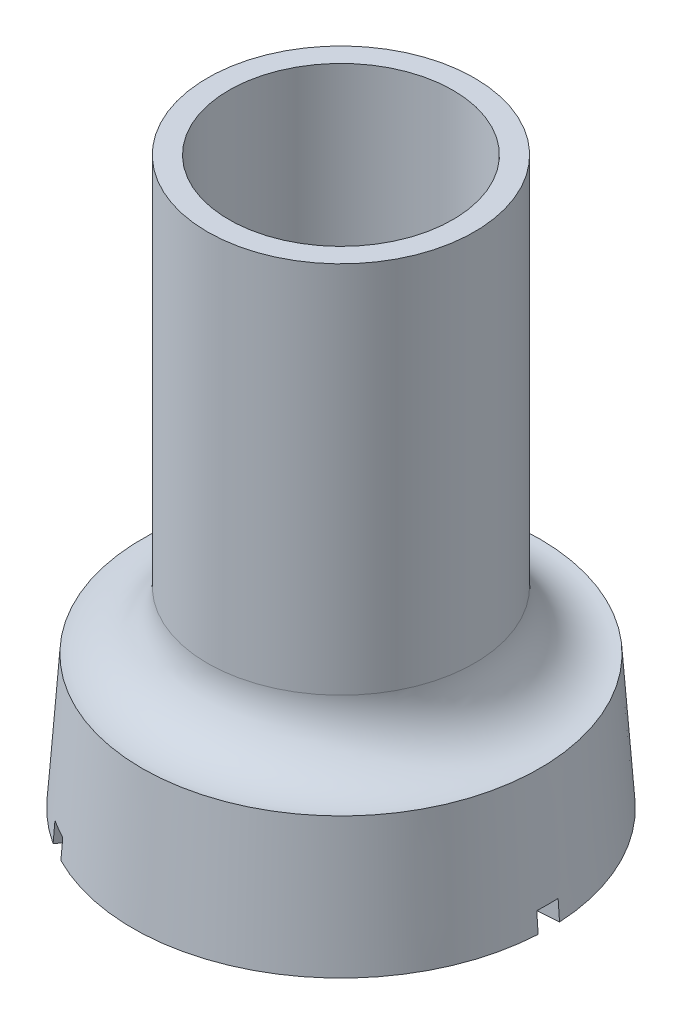
SolidWorks part; units mm, degrees
ref_plane "Płaszczyzna przednia" through (0, 0, 0) normal (0, 0, 1) x (1, 0, 0)
ref_plane "Płaszczyzna górna" through (0, 0, 0) normal (0, 1, 0) x (1, 0, 0)
ref_plane "Płaszczyzna prawa" through (0, 0, 0) normal (1, 0, 0) x (0, 0, -1)
sketch "Szkic2" plane through (0, 0, 0) normal (1, 0, 0) x (0, 0, -1)
  line L0 (0, 0) -> (0, 5.3) construction
  line L1 (0, 0) -> (1.95, 0) construction
  line L2 (1.95, 0) -> (1.7747, 2.5071) construction
  line L3 (0, 5.3) -> (1.25, 5.3) construction
  line L4 (1.25, 5.3) -> (1.25, 1.8)
  line L5 (1.8623, 1.2535) -> (1.95, 0)
  arc A0 (1.25, 1.8) -> (1.8623, 1.2535) centre (1.8, 1.8) ccw
  dimension "D6" = 0.55
  dimension "D1" = 5.3
  dimension "D2" = 1.95
  dimension "D3" = 4
  dimension "D4" = 1.25
  dimension "D5" = 3.5
revolve "Obrót-cienka ścianka3" add sketch "Szkic2" angle 360 about L0
sketch3d "Szkic 3D1"
  point P0 (1.687, 0.2884, -0.9372)
ref_plane "Płaszczyzna4" through (1.95, 0, 0) normal (1, 0, 0) x (0, 0, -1)
sketch "Szkic8" plane through (1.95, 0, 0) normal (1, 0, 0) x (0, 0, -1)
  line L0 (1.7505, -0.014) -> (-1.7505, -0.014) construction
  line L1 (0.1, -0.214) -> (-0.1, -0.214)
  line L2 (0.1, -0.214) -> (0.1, 0.186)
  line L3 (0.1, 0.186) -> (-0.1, 0.186)
  line L4 (-0.1, -0.214) -> (-0.1, 0.186)
  line L5 (0.1, -0.214) -> (-0.1, 0.186) construction
  line L6 (0.1, 0.186) -> (-0.1, -0.214) construction
  point P0 (0, -0.014)
  dimension "D1" = 0.4
  dimension "D2" = 0.2
extrude "Wytnij-wyciągnięcie11" cut sketch "Szkic8" against normal blind 0.26
pattern_circular "Szyk kołowy1" count 3 over 360 about axis through (0, 0, 0) along (0, 1, 0) of "Wytnij-wyciągnięcie11"
